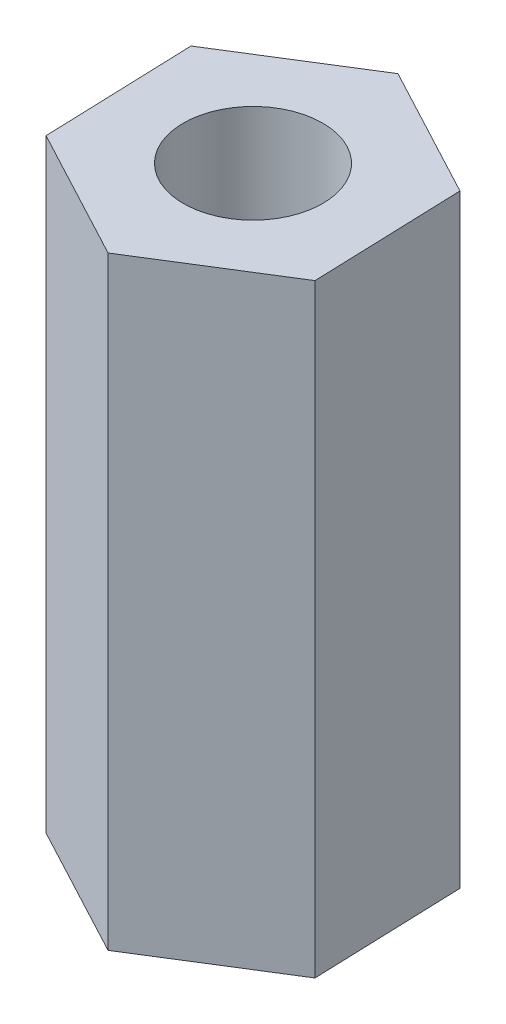
SolidWorks part; units mm, degrees
ref_plane "前视基准面" through (0, 0, 0) normal (0, 0, 1) x (1, 0, 0)
ref_plane "上视基准面" through (0, 0, 0) normal (0, 1, 0) x (1, 0, 0)
ref_plane "右视基准面" through (0, 0, 0) normal (1, 0, 0) x (0, 0, -1)
other "Configuration Table"
sketch "草图1" plane through (0, 0, 0) normal (0, 1, 0) x (1, 0, 0)
  line L1 (2.8541, -1.5191) -> (2.7426, 1.7121)
  line L2 (2.7426, 1.7121) -> (-0.1115, 3.2312)
  line L3 (-0.1115, 3.2312) -> (-2.8541, 1.5191)
  line L4 (-2.8541, 1.5191) -> (-2.7426, -1.7121)
  line L5 (-2.7426, -1.7121) -> (0.1115, -3.2312)
  line L6 (0.1115, -3.2312) -> (2.8541, -1.5191)
  circle A0 centre (0, 0) radius 2.8 construction
  circle A1 centre (0, 0) radius 1.5
extrude "凸台-拉伸1" add sketch "草图1" along normal blind 13
